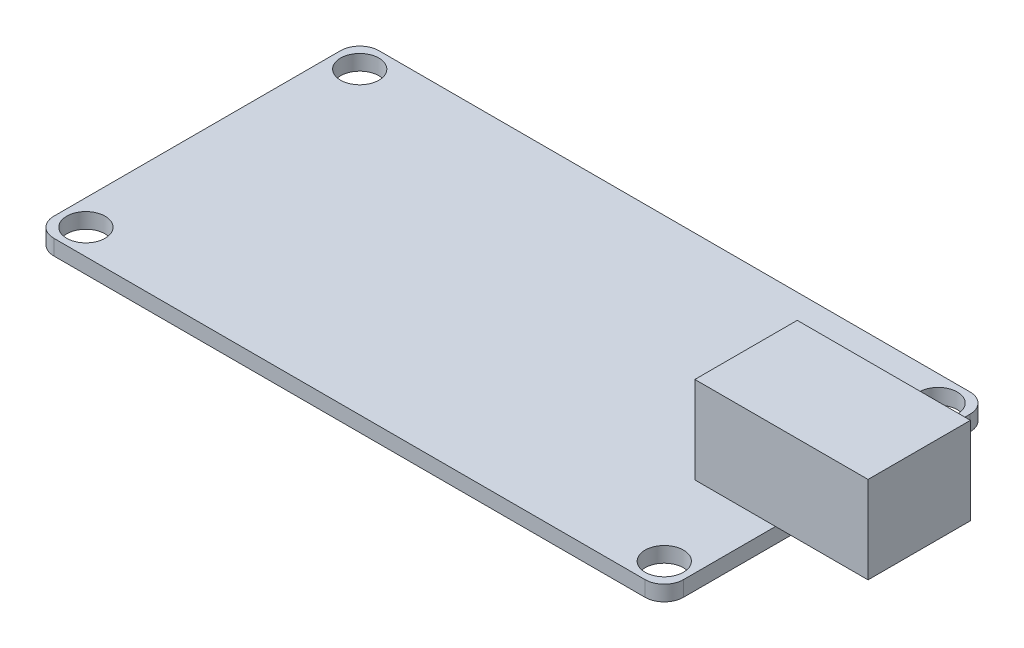
SolidWorks part; units mm, degrees
ref_plane "Plan de face" through (0, 0, 0) normal (0, 0, 1) x (1, 0, 0)
ref_plane "Plan de dessus" through (0, 0, 0) normal (0, 1, 0) x (1, 0, 0)
ref_plane "Plan de droite" through (0, 0, 0) normal (1, 0, 0) x (0, 0, -1)
sketch "Esquisse1" plane through (0, 0, 0) normal (0, 1, 0) x (1, 0, 0)
  line L0 (-24.6, 12.7) -> (-22.6, 12.7) construction
  line L1 (-24.6, -12.7) -> (24.6, -12.7)
  line L2 (-24.6, -12.7) -> (-24.6, 12.7)
  line L3 (-24.6, 12.7) -> (24.6, 12.7)
  line L4 (24.6, -12.7) -> (24.6, 12.7)
  line L5 (-24.6, -12.7) -> (24.6, 12.7) construction
  line L6 (-24.6, 12.7) -> (24.6, -12.7) construction
  line L7 (-22.6, 12.7) -> (-22.6, -12.7) construction
  line L8 (-24.6, 12.7) -> (-24.6, 10.7) construction
  line L9 (-24.6, 10.7) -> (24.6, 10.7) construction
  line L10 (24.6, 12.7) -> (22.6, 12.7) construction
  line L11 (22.6, 12.7) -> (22.6, -12.7) construction
  line L12 (24.6, -12.7) -> (24.6, -10.7) construction
  line L13 (24.6, -10.7) -> (-24.6, -10.7) construction
  circle A0 centre (22.6, 10.7) radius 1.5
  circle A1 centre (22.6, -10.7) radius 1.5
  circle A2 centre (-22.6, -10.7) radius 1.5
  circle A3 centre (-22.6, 10.7) radius 1.5
  point P0 (0, 0)
  dimension "D1" = 25.4
  dimension "D2" = 49.2
extrude "Boss.-Extru.1" add sketch "Esquisse1" along normal blind 1.2
fillet "Congé1" radius 1.5 1 edges at (24.6, 0.6, 12.7)
fillet "Congé2" radius 1.5 1 edges at (-24.6, 0.6, 12.7)
fillet "Congé3" radius 1.5 1 edges at (24.6, 0.6, -12.7)
fillet "Congé4" radius 1.5 1 edges at (-24.6, 0.6, -12.7)
sketch "Esquisse3" plane through (1.4308, 1.2, 0.9356) normal (0, 1, 0) x (1, 0, 0)
  line L0 (-26.0308, 0.9356) -> (23.6336, 0.9356) construction
  line L1 (30.4008, 4.9288) -> (16.8664, 4.9288)
  line L2 (30.4008, 4.9288) -> (30.4008, -3.0712)
  line L3 (30.4008, -3.0712) -> (16.8664, -3.0712)
  line L4 (16.8664, 4.9288) -> (16.8664, -3.0712)
  line L5 (-26.0308, 12.1356) -> (-26.0308, -10.2644) construction
  line L6 (30.4008, 0.9288) -> (16.8664, 0.9288) construction
  dimension "D1" = 8
extrude "Boss.-Extru.2" add sketch "Esquisse3" along normal blind 6.8
